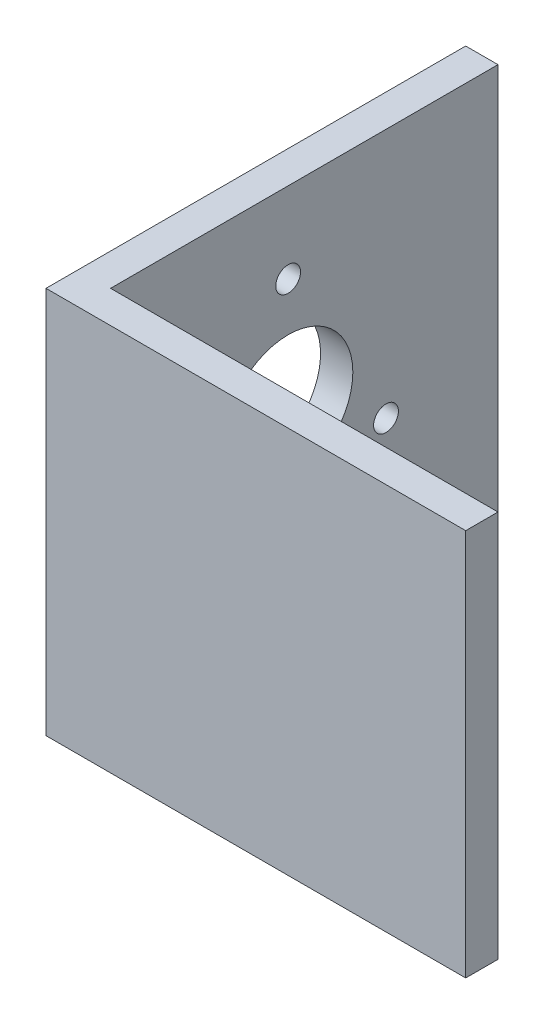
SolidWorks part; units mm, degrees
ref_plane "Front Plane" through (0, 0, 0) normal (0, 0, 1) x (1, 0, 0)
ref_plane "Top Plane" through (0, 0, 0) normal (0, 1, 0) x (1, 0, 0)
ref_plane "Right Plane" through (0, 0, 0) normal (1, 0, 0) x (0, 0, -1)
sketch "Sketch1" plane through (0, 0, 0) normal (0, 1, 0) x (1, 0, 0)
  line L0 (0, 38.1) -> (0, 0)
  line L1 (0, 0) -> (38.1, 0)
  dimension "D1" = 38.1
  dimension "D2" = 38.1
extrude "Extrude-Thin1" add sketch "Sketch1" along normal blind 38.1 thin
sketch "Sketch2" plane through (-3.175, 0, 0) normal (-1, 0, 0) x (0, 0, 1)
  line L0 (-38.1, 19.05) -> (3.175, 19.05) construction
  line L1 (-38.1, 38.1) -> (-38.1, 0) construction
  line L2 (3.175, 38.1) -> (3.175, 0) construction
  circle A0 centre (-17.4625, 19.05) radius 6.3627
  dimension "D1" = 12.7254
extrude "Cut-Extrude1" cut sketch "Sketch2" against normal through all
hole_wizard "#2 Clearance Hole1" positions "Sketch3" profile "Sketch4" hole size "#2" standard "ANSI Inch" end condition through all
sketch "Sketch3" plane through (-3.175, 0, 0) normal (-1, 0, 0) x (0, 0, 1)
  circle A0 centre (-17.4625, 19.05) radius 11.1125 construction
  point P5 (-17.4625, 30.1625)
  point P14 (-7.8388, 13.4938)
  point P15 (-27.0862, 13.4938)
  point P17 (-33.4385, 13.4917)
  point P18 (-13.9126, 15.3005)
  point P19 (0, 0)
  dimension "D1" = 22.225
  dimension "D2" = 3
sketch "Sketch4" plane through (-3.175, 13.4938, -27.0862) normal (0, 1, 0) x (0, 0, 1)
  line L0 (0, 0) -> (0, 41.275)
  line L1 (0, 41.275) -> (1.2192, 41.275)
  line L2 (1.2192, 41.275) -> (1.2192, 0)
  line L5 (1.2192, 0) -> (0, 0)
  line L11 (0, -6.35) -> (0, 107.95) construction
  dimension "Thru Hole Dia." = 2.4384
  dimension "Thru Hole Depth" = 41.275
